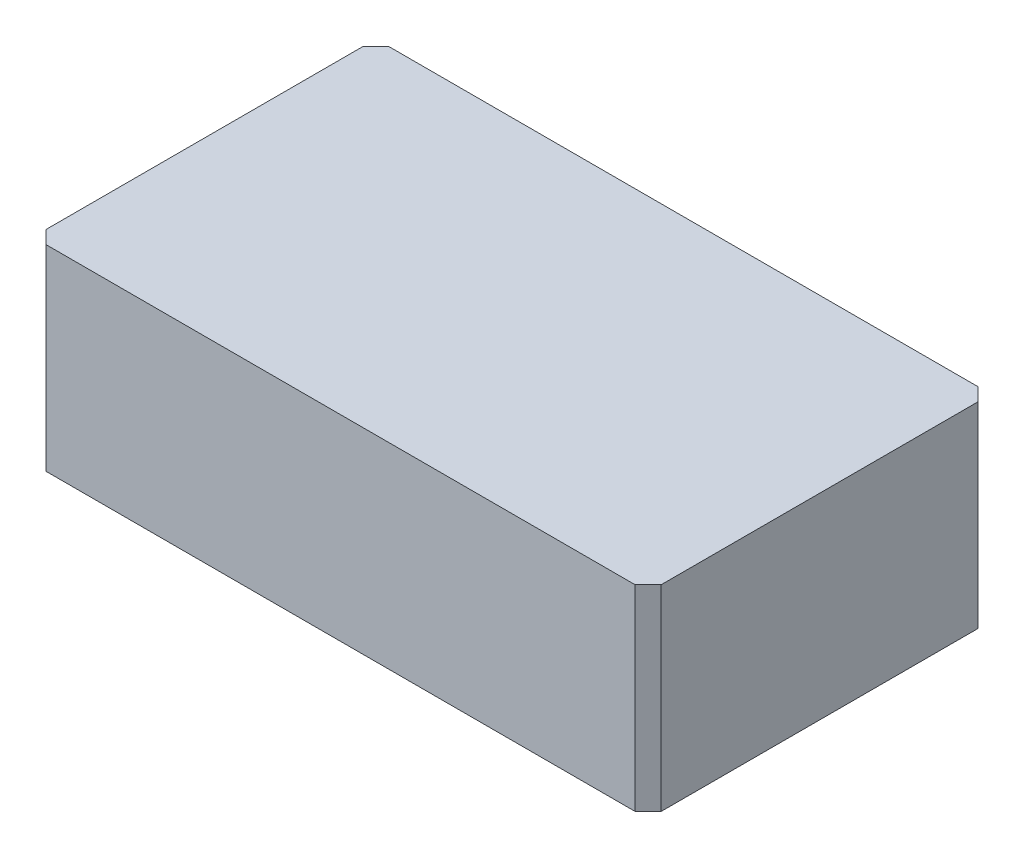
SolidWorks part; units mm, degrees
ref_plane "Front Plane" through (0, 0, 0) normal (0, 0, 1) x (1, 0, 0)
ref_plane "Top Plane" through (0, 0, 0) normal (0, 1, 0) x (1, 0, 0)
ref_plane "Right Plane" through (0, 0, 0) normal (1, 0, 0) x (0, 0, -1)
sketch "Sketch1" plane through (0, 0, 0) normal (0, 0, 1) x (1, 0, 0)
  line L1 (-19.7037, 1.1655) -> (27.2963, 1.1655)
  line L2 (-19.7037, 1.1655) -> (-19.7037, -13.8345)
  line L3 (-19.7037, -13.8345) -> (27.2963, -13.8345)
  line L4 (27.2963, 1.1655) -> (27.2963, -13.8345)
  dimension "D1" = 47
  dimension "D2" = 15
extrude "Boss-Extrude1" add sketch "Sketch1" along normal blind 26.2
chamfer "Chamfer1" distance 1 angle 45 4 edges at (27.2963, -6.3345, 26.2) (-19.7037, -6.3345, 26.2) (-19.7037, -6.3345, 0) (27.2963, -6.3345, 0)
